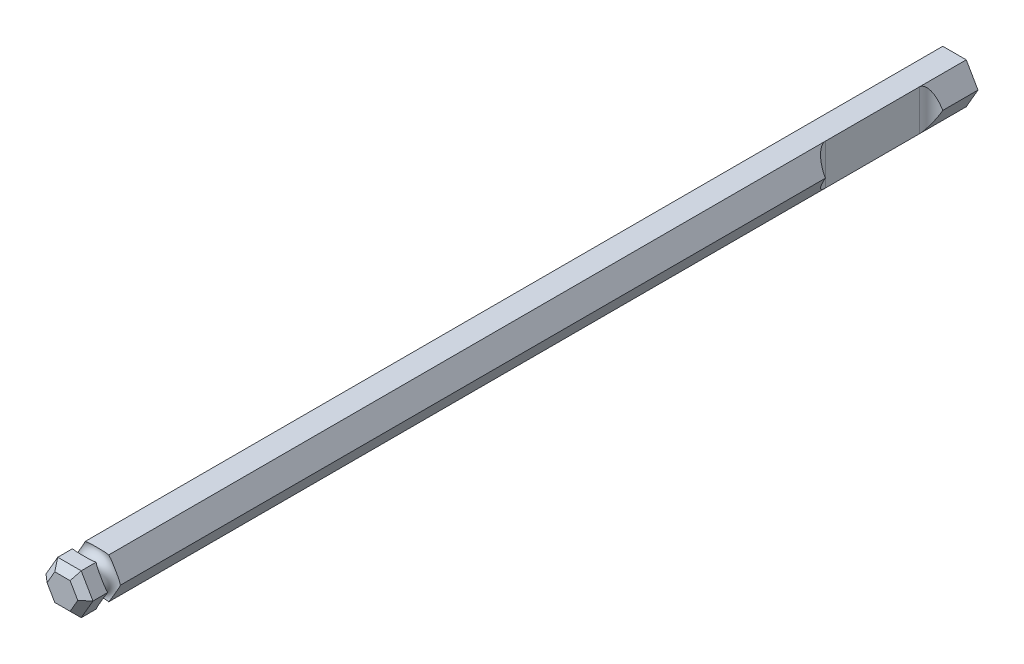
SolidWorks part; units mm, degrees
ref_plane "Alzado" through (0, 0, 0) normal (0, 0, 1) x (1, 0, 0)
ref_plane "Planta" through (0, 0, 0) normal (0, 1, 0) x (1, 0, 0)
ref_plane "Vista lateral" through (0, 0, 0) normal (1, 0, 0) x (0, 0, -1)
sketch "Croquis1" plane through (0, 0, 0) normal (0, 0, 1) x (1, 0, 0)
  line L1 (1.25, -2.1651) -> (2.5, 0)
  line L2 (2.5, 0) -> (1.25, 2.1651)
  line L3 (1.25, 2.1651) -> (-1.25, 2.1651)
  line L4 (-1.25, 2.1651) -> (-2.5, 0)
  line L5 (-2.5, 0) -> (-1.25, -2.1651)
  line L6 (-1.25, -2.1651) -> (1.25, -2.1651)
  circle A0 centre (0, 0) radius 2.1651 construction
  dimension "D1" = 2.5
extrude "Saliente-Extruir1" add sketch "Croquis1" against normal blind 95
chamfer "Chaflán1" distance 0.75 angle 45 6 edges at (-1.875, -1.0825, 0) (-1.875, 1.0825, 0) (0, 2.1651, 0) (1.875, 1.0825, 0) (1.875, -1.0825, 0) (0, -2.1651, 0)
sketch "Croquis2" plane through (0, 0, 0) normal (1, 0, 0) x (0, 0, -1)
  line L0 (95, 2.1651) -> (0.75, 2.1651) construction
  line L1 (0, 0) -> (-1.8565, 0) construction
  circle A0 centre (3, 2.1651) radius 0.75
  dimension "D1" = 1.5
  dimension "D2" = 3
revolve "Cortar-Revolución1" cut sketch "Croquis2" angle 360 about L1
sketch "Croquis5" plane through (0, 0, 0) normal (0, 1, 0) x (1, 0, 0)
  line L0 (-2.5, 90) -> (-2.5, 80) construction
  line L1 (-2.5, 95) -> (-2.5, 3.6711) construction
  line L2 (-1.25, 90) -> (-1.25, 80)
  line L3 (-3.75, 90) -> (-3.75, 80)
  line L5 (-1.25, 95) -> (-1.25, 3.6711) construction
  line L6 (1.25, 95) -> (-1.25, 95) construction
  line L7 (0, 95) -> (0, 76.9579) construction
  line L8 (2.5, 90) -> (2.5, 80) construction
  line L9 (1.25, 90) -> (1.25, 80)
  line L10 (3.75, 90) -> (3.75, 80)
  arc A0 (-1.25, 90) -> (-3.75, 90) centre (-2.5, 90) ccw
  arc A1 (-3.75, 80) -> (-1.25, 80) centre (-2.5, 80) ccw
  arc A2 (1.25, 90) -> (3.75, 90) centre (2.5, 90) cw
  arc A3 (3.75, 80) -> (1.25, 80) centre (2.5, 80) cw
  point P4 (-2.5, 85)
  point P18 (2.5, 85)
  dimension "D1" = 10
  dimension "D2" = 5
extrude "Cortar-Extruir1" cut sketch "Croquis5" against normal through all both and the other way through all
